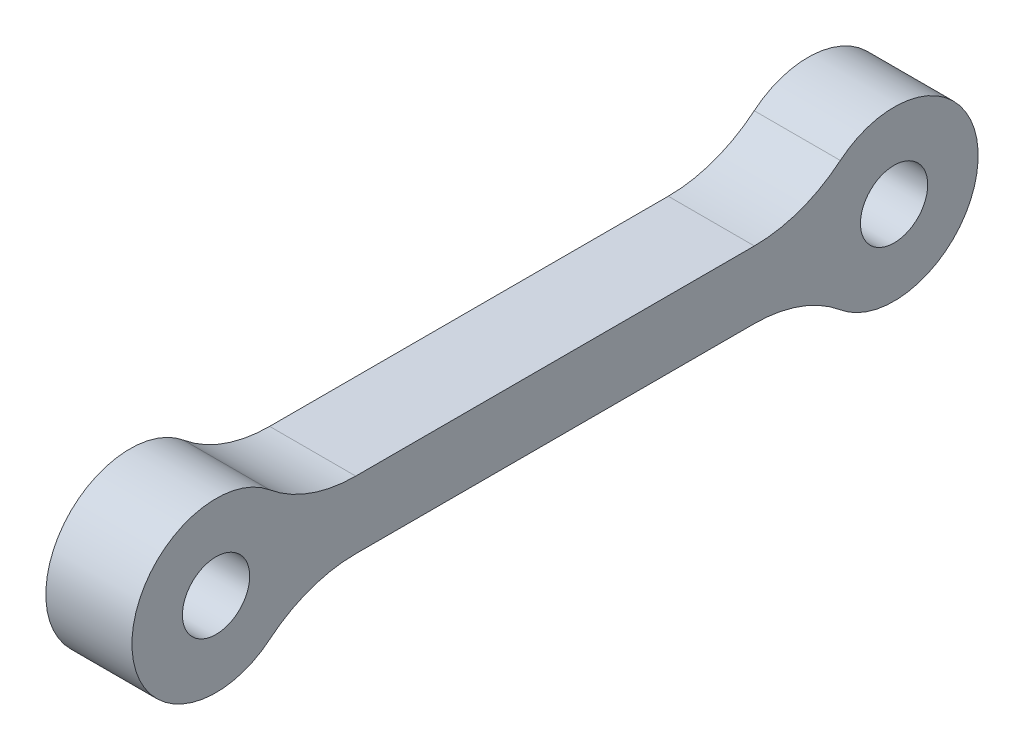
SolidWorks part; units mm, degrees
material "6061-T6 (SS)"
ref_plane "Front Plane" through (0, 0, 0) normal (0, 0, 1) x (1, 0, 0)
ref_plane "Top Plane" through (0, 0, 0) normal (0, 1, 0) x (1, 0, 0)
ref_plane "Right Plane" through (0, 0, 0) normal (1, 0, 0) x (0, 0, -1)
sketch "Sketch1" plane through (0, 0, 0) normal (1, 0, 0) x (0, 0, -1)
  line L3 (3.6374, 1.5875) -> (28.3626, 1.5875)
  line L5 (3.6374, -1.5875) -> (28.3626, -1.5875)
  circle A2 centre (0, 0) radius 1.5875
  circle A3 centre (32, 0) radius 1.5875
  arc A4 (3.6374, 1.5875) -> (3.6374, -1.5875) centre (0, 0) ccw
  arc A5 (28.3626, -1.5875) -> (28.3626, 1.5875) centre (32, 0) ccw
  dimension "D1" = 32
  dimension "D3" = 3.175
  dimension "D2" = 7.9375
  dimension "D4" = 3.175
extrude "Boss-Extrude1" add sketch "Sketch1" along normal blind 4.064
fillet "Fillet1" radius 6.35 4 edges at (2.032, 1.5875, -28.3626) (2.032, -1.5875, -28.3626) (2.032, -1.5875, -3.6374) (2.032, 1.5875, -3.6374)
